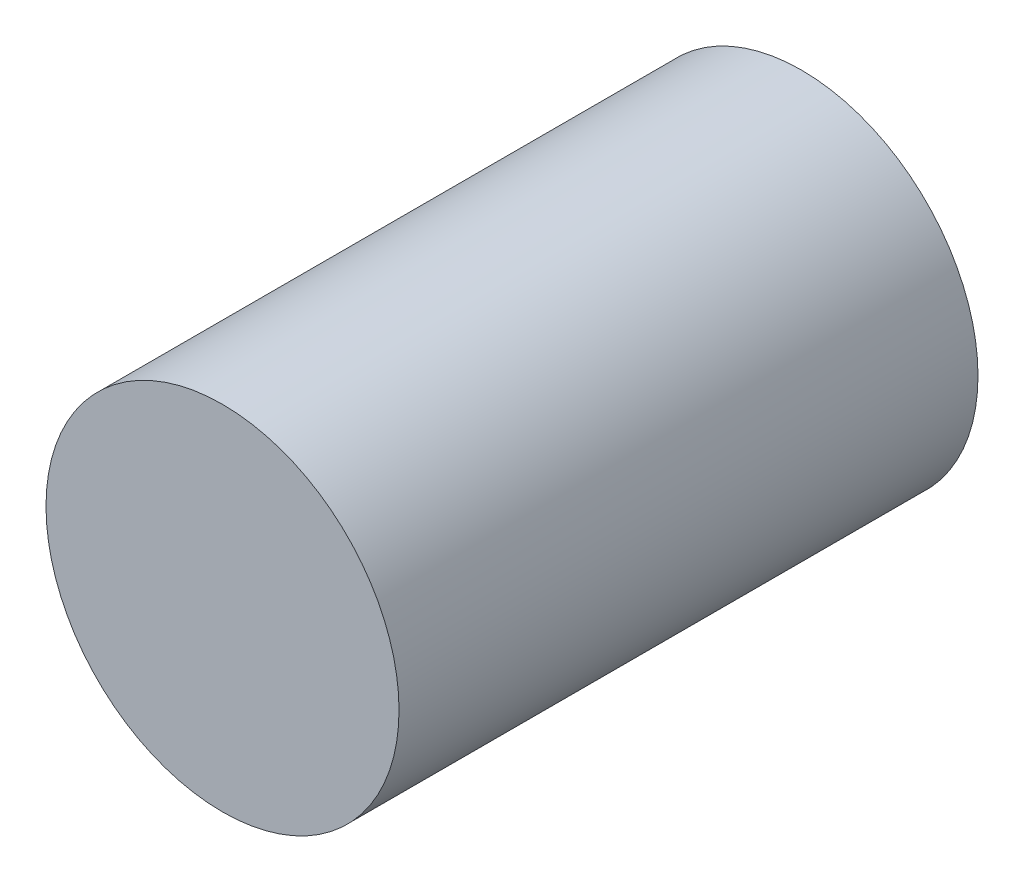
SolidWorks part; units mm, degrees
ref_plane "Front Plane" through (0, 0, 0) normal (0, 0, 1) x (1, 0, 0)
ref_plane "Top Plane" through (0, 0, 0) normal (0, 1, 0) x (1, 0, 0)
ref_plane "Right Plane" through (0, 0, 0) normal (1, 0, 0) x (0, 0, -1)
sketch "Sketch1" plane through (0, 0, 0) normal (0, 0, 1) x (1, 0, 0)
  circle A0 centre (0, 0) radius 25
  dimension "D1" = 50
extrude "Boss-Extrude1" add sketch "Sketch1" along normal blind 82
